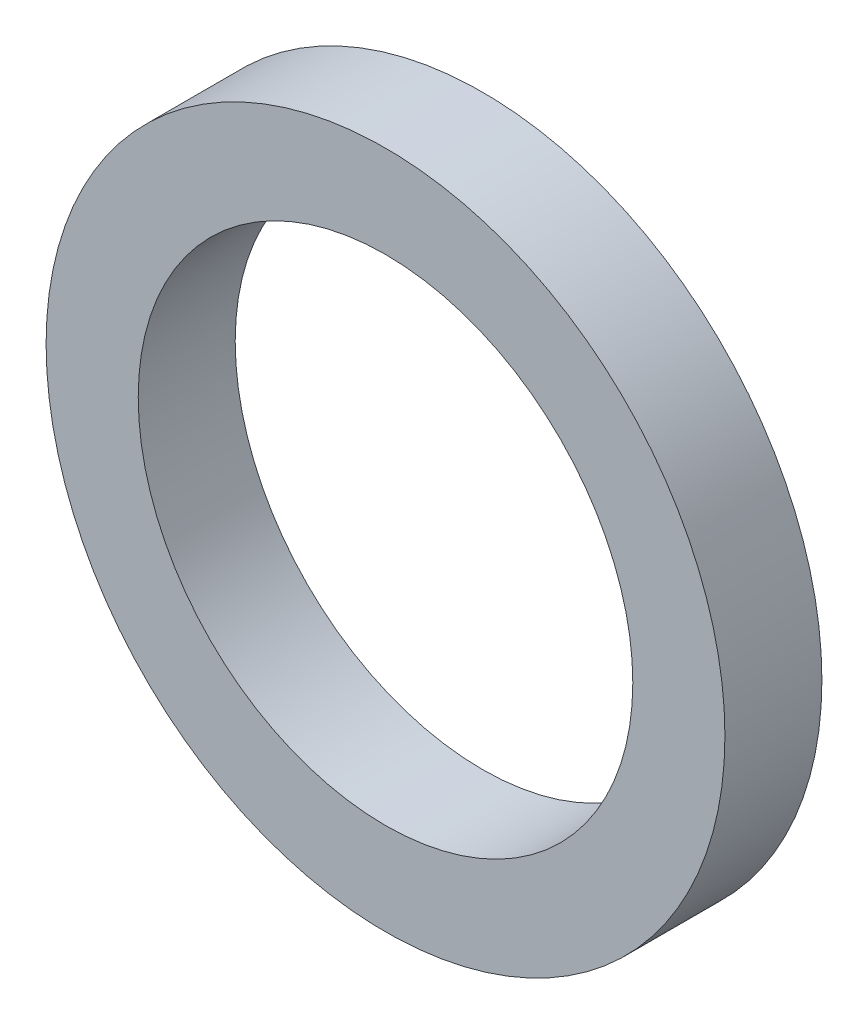
SolidWorks part; units mm, degrees
ref_plane "Front Plane" through (0, 0, 0) normal (0, 0, 1) x (1, 0, 0)
ref_plane "Top Plane" through (0, 0, 0) normal (0, 1, 0) x (1, 0, 0)
ref_plane "Right Plane" through (0, 0, 0) normal (1, 0, 0) x (0, 0, -1)
sketch "Sketch1" plane through (0, 0, 0) normal (0, 0, 1) x (1, 0, 0)
  circle A0 centre (0, 0) radius 3.5
  circle A1 centre (0, 0) radius 2.55
  dimension "D1" = 5.1
  dimension "D2" = 7
extrude "Boss-Extrude1" add sketch "Sketch1" along normal mid plane 1
